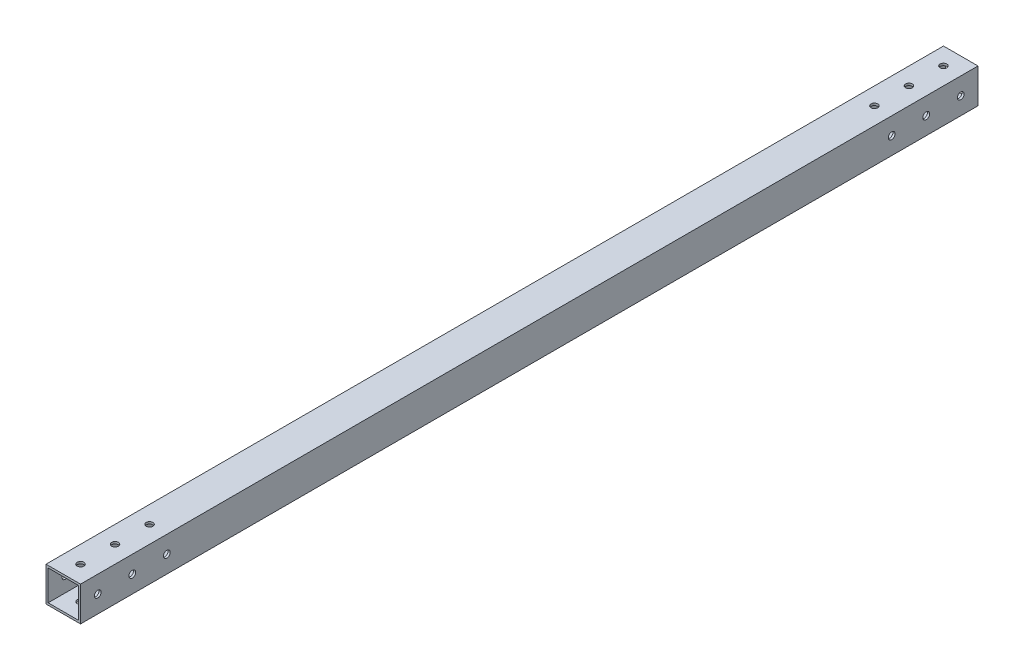
SolidWorks part; units mm, degrees
ref_plane "Front Plane" through (0, 0, 0) normal (0, 0, 1) x (1, 0, 0)
ref_plane "Top Plane" through (0, 0, 0) normal (0, 1, 0) x (1, 0, 0)
ref_plane "Right Plane" through (0, 0, 0) normal (1, 0, 0) x (0, 0, -1)
sketch "Sketch5" plane through (0, 0, 0) normal (0, 0, 1) x (1, 0, 0)
  line L1 (0, 0) -> (25.4, 0)
  line L2 (0, 0) -> (0, 25.4)
  line L3 (0, 25.4) -> (25.4, 25.4)
  line L4 (25.4, 0) -> (25.4, 25.4)
  dimension "D1" = 25.4
  dimension "D2" = 25.4
extrude "Boss-Extrude2" add sketch "Sketch5" along normal mid plane 660.4
shell "Shell3" thickness 1.5875
sketch "Sketch6" plane through (0, 25.4, 0) normal (0, 1, 0) x (1, 0, 0)
  line L0 (25.4, 330.2) -> (0, 330.2) construction
  line L1 (0, -330.2) -> (0, 330.2) construction
  circle A0 centre (12.7, 317.5) radius 2.4892
  circle A1 centre (12.7, 292.1) radius 2.4892
  circle A2 centre (12.7, 266.7) radius 2.4892
  dimension "D1" = 4.9784
  dimension "D2" = 25.4
  dimension "D3" = 25.4
  dimension "D4" = 12.7
  dimension "D5" = 12.7
extrude "Cut-Extrude2" cut sketch "Sketch6" against normal through all
sketch "Sketch7" plane through (25.4, 0, 0) normal (1, 0, 0) x (0, 0, -1)
  line L0 (330.2, 0) -> (330.2, 25.4) construction
  line L1 (-330.2, 0) -> (330.2, 0) construction
  circle A0 centre (292.1, 12.7) radius 2.4892
  circle A1 centre (317.5, 12.7) radius 2.4892
  circle A2 centre (266.7, 12.7) radius 2.4892
  dimension "D1" = 4.9784
  dimension "D2" = 25.4
  dimension "D3" = 25.4
  dimension "D4" = 12.7
  dimension "D5" = 12.7
extrude "Cut-Extrude3" cut sketch "Sketch7" against normal through all
mirror "Mirror2" about plane through (0, 0, 0) normal (0, 0, 1) of "Cut-Extrude3", "Cut-Extrude2"
